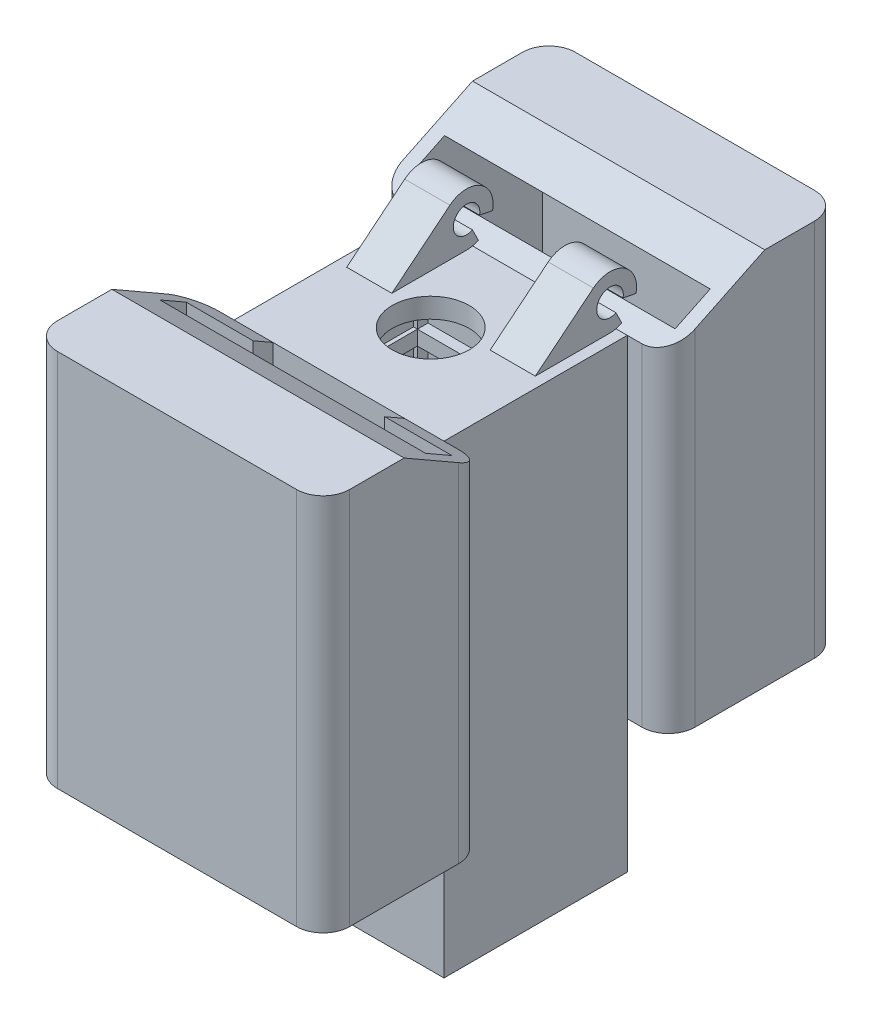
SolidWorks part; units mm, degrees
ref_plane "前视基准面" through (0, 0, 0) normal (0, 0, 1) x (1, 0, 0)
ref_plane "上视基准面" through (0, 0, 0) normal (0, 1, 0) x (1, 0, 0)
ref_plane "右视基准面" through (0, 0, 0) normal (1, 0, 0) x (0, 0, -1)
sketch "草图1" plane through (0, 0, 0) normal (0, 1, 0) x (1, 0, 0)
  line L1 (-4.3182, 2.8513) -> (8.4818, 2.8513)
  line L2 (-4.3182, 2.8513) -> (-4.3182, -7.9487)
  line L3 (-4.3182, -7.9487) -> (8.4818, -7.9487)
  line L4 (8.4818, 2.8513) -> (8.4818, -7.9487)
  dimension "D1" = 12.8
extrude "凸台-拉伸1" add sketch "草图1" along normal blind 1.5
sketch "草图2" plane through (0, 1.5, 0) normal (0, 1, 0) x (1, 0, 0)
  circle A0 centre (2.0818, -2.5487) radius 2.9
extrude "切除-拉伸1" cut sketch "草图2" against normal up to next
sketch "草图3" plane through (0, 1.5, 0) normal (0, 1, 0) x (1, 0, 0)
  line L0 (-4.3182, -2.5487) -> (9.9215, -2.5487) construction
  line L1 (-4.3182, 2.8513) -> (8.4818, 2.8513)
  line L2 (-4.3182, 2.8513) -> (-4.3182, 4.3513)
  line L3 (-4.3182, 4.3513) -> (8.4818, 4.3513)
  line L4 (8.4818, 2.8513) -> (8.4818, 4.3513)
  line L5 (-4.3182, 2.8513) -> (-4.3182, -7.9487) construction
  line L6 (8.4818, -7.9487) -> (8.4818, -9.4487)
  line L7 (-4.3182, -9.4487) -> (8.4818, -9.4487)
  line L8 (-4.3182, -7.9487) -> (-4.3182, -9.4487)
  line L9 (-4.3182, -7.9487) -> (8.4818, -7.9487)
  line L10 (2.0818, 2.8513) -> (2.0818, -17.0231) construction
  line L11 (-4.3182, 4.3513) -> (-5.8182, 4.3513)
  line L12 (-4.3182, 4.3513) -> (-4.3182, -9.4487)
  line L13 (-4.3182, -9.4487) -> (-5.8182, -9.4487)
  line L14 (-5.8182, 4.3513) -> (-5.8182, -9.4487)
  line L15 (8.4818, -9.4487) -> (9.9818, -9.4487)
  line L16 (9.9818, 4.3513) -> (9.9818, -9.4487)
  line L17 (8.4818, 4.3513) -> (8.4818, -9.4487)
  line L18 (8.4818, 4.3513) -> (9.9818, 4.3513)
  line M6 (-4.3182, 2.8513) -> (-4.3182, -7.9487)
  line M7 (-4.3182, -7.9487) -> (8.4818, -7.9487)
  line M8 (8.4818, -7.9487) -> (8.4818, 2.8513)
  line M9 (8.4818, 2.8513) -> (-4.3182, 2.8513)
  dimension "D1" = 1.5
  dimension "D2" = 12.8
  dimension "D3" = 1.5
extrude "凸台-拉伸2" add sketch "草图3" against normal blind 35 contours L11 L14 L13 L8 L2 M6 | L4 L3 L2 M9 | L18 L4 L6 L15 L16 M8 | L8 L7 L6 M7
sketch "草图6" plane through (0, -33.5, 0) normal (0, -1, 0) x (1, 0, 0)
  line L0 (9.9818, -4.3513) -> (-5.8182, -4.3513) construction
  line L1 (-4.3182, -2.8513) -> (8.4818, -2.8513)
  line L2 (-4.3182, -2.8513) -> (-4.3182, -4.3513)
  line L3 (-4.3182, -4.3513) -> (8.4818, -4.3513)
  line L4 (8.4818, -2.8513) -> (8.4818, -4.3513)
extrude "切除-拉伸2" cut sketch "草图6" against normal blind 10
sketch "草图9" plane through (9.9818, 0, 0) normal (1, 0, 0) x (0, 0, -1)
  line L0 (4.3513, 1.5) -> (-9.4487, 1.5) construction
  line L3 (4.3513, -33.5) -> (4.3513, 1.5) construction
  line L5 (4.295, 2.6038) -> (4.7386, 1.7076)
  line L6 (4.8305, 3.2974) -> (5.8108, 3.0999)
  line L10 (-1.7717, 1.5) -> (3.8513, 1.5)
  line L11 (2.5983, 5.0589) -> (-1.7717, 1.5)
  arc A0 (3.8513, 1.5) -> (4.7386, 1.7076) centre (3.8513, 3.5) ccw
  arc A1 (4.8305, 3.2974) -> (4.295, 2.6038) centre (3.8513, 3.5) ccw
  arc A2 (5.8108, 3.0999) -> (2.5983, 5.0589) centre (3.8513, 3.5) ccw
  dimension "D1" = 4
  dimension "D3" = 2
  dimension "D2" = 2
  dimension "D4" = 0.5
extrude "凸台-拉伸4" add sketch "草图9" against normal blind 15.8
sketch "草图10" plane through (0, 0, -4.3513) normal (0, 0, -1) x (-1, 0, 0)
  line L0 (-2.0818, 8.9772) -> (-2.0818, 5.5) construction
  line L1 (-9.9818, 1.5) -> (5.8182, 1.5) construction
  line L2 (1.6182, 1.5) -> (-5.7818, 1.5)
  line L4 (1.6182, 5.5) -> (-5.7818, 5.5)
  line L5 (-5.7818, 1.5) -> (-5.7818, 5.5)
  line L6 (1.6182, 1.5) -> (1.6182, 5.5)
  line L7 (-2.0818, 1.5) -> (-2.0818, -41.1456) construction
  line L8 (5.8182, 1.5) -> (5.0182, 1.5)
  line L9 (-9.9818, 1.5) -> (-9.1818, 1.5)
  line L10 (-9.9818, 1.5) -> (-9.9818, 5.5)
  line L11 (-9.9818, 5.5) -> (-9.1818, 5.5)
  line L12 (-9.1818, 1.5) -> (-9.1818, 5.5)
  line L13 (5.0182, 1.5) -> (5.0182, 5.5)
  line L14 (5.8182, 5.5) -> (5.0182, 5.5)
  line L15 (5.8182, 1.5) -> (5.8182, 5.5)
  dimension "D1" = 3.7
  dimension "D2" = 0.8
  dimension "D3" = 4
  dimension "D4" = 4
extrude "切除-拉伸3" cut sketch "草图10" against normal through all both and the other way through all
sketch "草图12" plane through (0, 0, -4.3513) normal (0, 0, -1) x (-1, 0, 0)
  line L1 (-10.6818, 5.5) -> (6.3182, 5.5)
  line L2 (-10.6818, 5.5) -> (-10.6818, -23.5)
  line L3 (-10.6818, -23.5) -> (6.3182, -23.5)
  line L4 (6.3182, 5.5) -> (6.3182, -23.5)
  line L5 (4.3182, -23.5) -> (-8.4818, -23.5) construction
  line L6 (5.8182, -33.5) -> (5.8182, 1.5) construction
  dimension "D1" = 17
  dimension "D2" = 29
  dimension "D3" = 0
  dimension "D4" = 0.5
sketch "草图16" plane through (0, 0, 0) normal (0, -1, 0) x (1, 0, 0)
  line L1 (-3.9182, 7.5487) -> (8.0818, 7.5487)
  line L2 (-3.9182, 7.5487) -> (-3.9182, -2.4513)
  line L3 (-3.9182, -2.4513) -> (8.0818, -2.4513)
  line L4 (8.0818, 7.5487) -> (8.0818, -2.4513)
  line L5 (-3.9182, 7.5487) -> (8.0818, -2.4513) construction
  line L6 (-3.9182, -2.4513) -> (8.0818, 7.5487) construction
  point P2 (2.0818, 2.5487)
  dimension "D1" = 12
  dimension "D2" = 10
sketch "草图17" plane through (-5.8182, 0, 0) normal (-1, 0, 0) x (0, 0, 1)
  line L0 (-4.3513, -33.5) -> (-4.3513, 1.5) construction
  line L1 (-4.3513, -23.5) -> (-17.3513, -23.5)
  line L2 (-4.3513, -23.5) -> (-4.3513, 1.5)
  line L3 (-11.6013, 5) -> (-17.3513, 5)
  line L4 (-17.3513, -23.5) -> (-17.3513, 5)
  line L5 (-4.3513, -33.5) -> (9.4487, -33.5) construction
  line L6 (-11.6013, 5) -> (-4.3513, 1.5)
  dimension "D1" = 28.5
  dimension "D2" = 13
  dimension "D3" = 10
extrude "凸台-拉伸5" add sketch "草图17" along normal blind 3.1 and the other way blind 18.9
sketch "草图18" plane through (0, -23.5, 0) normal (0, -1, 0) x (1, 0, 0)
  line L8 (-8.9182, -17.3513) -> (-8.9182, -4.3513) construction
  line L9 (-7.9182, -5.8513) -> (12.0818, -5.8513)
  line L10 (-7.9182, -5.8513) -> (-7.9182, -15.8513)
  line L11 (-7.9182, -15.8513) -> (12.0818, -15.8513)
  line L12 (12.0818, -5.8513) -> (12.0818, -15.8513)
  line L13 (13.0818, -17.3513) -> (13.0818, -4.3513) construction
  line L14 (13.0818, -4.3513) -> (9.9818, -4.3513) construction
  line L15 (13.0818, -17.3513) -> (-8.9182, -17.3513) construction
  dimension "D1" = 1
  dimension "D2" = 1
  dimension "D3" = 1.5
  dimension "D4" = 1.5
extrude "切除-拉伸4" cut sketch "草图18" against normal blind 27
sketch "草图20" plane through (0, 0, -2.8513) normal (0, 0, 1) x (1, 0, 0)
  line L0 (8.4818, -23.5) -> (8.4818, 0) construction
  line L1 (8.4818, -11.75) -> (-4.3182, -11.75)
  line L2 (8.4818, -11.75) -> (8.4818, -23.5)
  line L3 (8.4818, -23.5) -> (-4.3182, -23.5)
  line L4 (-4.3182, -11.75) -> (-4.3182, -23.5)
extrude "切除-拉伸5" cut sketch "草图20" against normal up to next
fillet "圆角3" radius 2 4 edges at (13.0818, -11, -4.3513) (13.0818, -9.25, -17.3513) (-8.9182, -9.25, -17.3513) (-8.9182, -11, -4.3513)
sketch "草图21" plane through (0, 0, 7.9487) normal (0, 0, -1) x (-1, 0, 0)
  line L1 (-8.4818, 0) -> (4.3182, 0)
  line L2 (-8.4818, 0) -> (-8.4818, -33.5)
  line L3 (-8.4818, -33.5) -> (4.3182, -33.5)
  line L4 (4.3182, 0) -> (4.3182, -33.5)
extrude "凸台-拉伸6" add sketch "草图21" along normal blind 0.8
sketch "草图22" plane through (0, 0, 7.1487) normal (0, 0, -1) x (-1, 0, 0)
  line L0 (4.3182, -33.5) -> (4.3182, 0) construction
  line L1 (-8.4818, -33.5) -> (4.3182, -33.5)
  line L2 (-8.4818, -33.5) -> (-8.4818, -23.5)
  line L3 (-8.4818, -23.5) -> (4.3182, -23.5)
  line L4 (4.3182, -33.5) -> (4.3182, -23.5)
  dimension "D1" = 10
extrude "切除-拉伸6" cut sketch "草图22" against normal blind 0.8
sketch "草图23" plane through (0, 0, 7.1487) normal (0, 0, -1) x (-1, 0, 0)
  line L0 (-8.4818, 0) -> (-8.4818, -23.5) construction
  line L1 (-8.4818, -2.5) -> (4.3182, -2.5)
  line L2 (-8.4818, -2.5) -> (-8.4818, -4.5)
  line L3 (-8.4818, -4.5) -> (4.3182, -4.5)
  line L4 (4.3182, -2.5) -> (4.3182, -4.5)
  line L5 (4.3182, -23.5) -> (4.3182, 0) construction
  line L6 (4.3182, 0) -> (-8.4818, 0) construction
  dimension "D1" = 2.5
  dimension "D2" = 4.5
extrude "切除-拉伸7" cut sketch "草图23" against normal blind 0.8
sketch "草图25" plane through (0, 0, -2.8513) normal (0, 0, 1) x (1, 0, 0)
  line L0 (-4.3182, -11.75) -> (-4.3182, 0) construction
  line L1 (-4.3182, -2.5) -> (8.4818, -2.5)
  line L2 (-4.3182, -2.5) -> (-4.3182, -4.5)
  line L3 (-4.3182, -4.5) -> (8.4818, -4.5)
  line L4 (8.4818, -2.5) -> (8.4818, -4.5)
  line L5 (8.4818, -11.75) -> (8.4818, 0) construction
  line L6 (8.4818, 0) -> (-4.3182, 0) construction
  dimension "D1" = 2.5
  dimension "D2" = 4.5
extrude "切除-拉伸8" cut sketch "草图25" against normal blind 0.8
sketch "草图26" plane through (0, 0, 7.1487) normal (0, 0, -1) x (-1, 0, 0)
  line L0 (-8.4818, -4.5) -> (-8.4818, -23.5) construction
  line L1 (-8.4818, -5.6) -> (4.3182, -5.6)
  line L2 (-8.4818, -5.6) -> (-8.4818, -7.6)
  line L3 (-8.4818, -7.6) -> (4.3182, -7.6)
  line L4 (4.3182, -5.6) -> (4.3182, -7.6)
  line L5 (4.3182, -23.5) -> (4.3182, -4.5) construction
  line L6 (4.3182, 0) -> (-8.4818, 0) construction
  dimension "D1" = 5.6
  dimension "D2" = 7.6
extrude "切除-拉伸9" cut sketch "草图26" against normal blind 0.8
sketch "草图27" plane through (0, 0, -2.8513) normal (0, 0, 1) x (1, 0, 0)
  line L0 (-4.3182, -11.75) -> (-4.3182, -4.5) construction
  line L1 (-4.3182, -5.6) -> (8.4818, -5.6)
  line L2 (-4.3182, -5.6) -> (-4.3182, -7.6)
  line L3 (-4.3182, -7.6) -> (8.4818, -7.6)
  line L4 (8.4818, -5.6) -> (8.4818, -7.6)
  line L5 (8.4818, -11.75) -> (8.4818, -4.5) construction
  line L6 (8.4818, 0) -> (-4.3182, 0) construction
  dimension "D1" = 5.6
  dimension "D2" = 7.6
extrude "切除-拉伸10" cut sketch "草图27" against normal blind 0.8
sketch "草图28" plane through (-4.3182, 0, 0) normal (1, 0, 0) x (0, 0, -1)
  line L1 (-7.1487, -5.6) -> (2.8513, -5.6)
  line L2 (-7.1487, -5.6) -> (-7.1487, -7.6)
  line L3 (-7.1487, -7.6) -> (2.8513, -7.6)
  line L4 (2.8513, -5.6) -> (2.8513, -7.6)
  line L5 (-7.1487, -2.5) -> (2.8513, -2.5)
  line L6 (-7.1487, -2.5) -> (-7.1487, -4.5)
  line L7 (-7.1487, -4.5) -> (2.8513, -4.5)
  line L8 (2.8513, -2.5) -> (2.8513, -4.5)
extrude "切除-拉伸11" cut sketch "草图28" against normal blind 0.3
sketch "草图29" plane through (8.4818, 0, 0) normal (-1, 0, 0) x (0, 0, 1)
  line L1 (-2.8513, -2.5) -> (7.1487, -2.5)
  line L2 (-2.8513, -2.5) -> (-2.8513, -4.5)
  line L3 (-2.8513, -4.5) -> (7.1487, -4.5)
  line L4 (7.1487, -2.5) -> (7.1487, -4.5)
  line L5 (-2.8513, -5.6) -> (7.1487, -5.6)
  line L6 (-2.8513, -5.6) -> (-2.8513, -7.6)
  line L7 (-2.8513, -7.6) -> (7.1487, -7.6)
  line L8 (7.1487, -5.6) -> (7.1487, -7.6)
extrude "切除-拉伸12" cut sketch "草图29" against normal blind 0.3
sketch "草图30" plane through (0, 0, 9.4487) normal (0, 0, 1) x (1, 0, 0)
  line L1 (-8.9182, -23.5) -> (13.0818, -23.5)
  line L2 (-8.9182, -23.5) -> (-8.9182, 5)
  line L3 (-8.9182, 5) -> (13.0818, 5)
  line L4 (13.0818, -23.5) -> (13.0818, 5)
extrude "凸台-拉伸7" add sketch "草图30" along normal blind 12.2
sketch "草图32" plane through (0, -23.5, 0) normal (0, -1, 0) x (1, 0, 0)
  line L0 (-8.9182, 21.6487) -> (13.0818, 21.6487) construction
  line L1 (-7.9182, 20.1487) -> (12.0818, 20.1487)
  line L2 (-7.9182, 20.1487) -> (-7.9182, 10.9487)
  line L3 (-7.9182, 10.9487) -> (12.0818, 10.9487)
  line L4 (12.0818, 20.1487) -> (12.0818, 10.9487)
  line L5 (13.0818, 21.6487) -> (13.0818, 9.4487) construction
  line L6 (-8.9182, 21.6487) -> (-8.9182, 9.4487) construction
  line L7 (-5.8182, 9.4487) -> (9.9818, 9.4487) construction
  dimension "D1" = 1.5
  dimension "D2" = 1
  dimension "D3" = 1
  dimension "D4" = 1.5
extrude "切除-拉伸13" cut sketch "草图32" against normal blind 27
sketch "草图33" plane through (13.0818, 0, 0) normal (1, 0, 0) x (0, 0, -1)
  line L0 (-15.5487, 5) -> (-9.4487, 1.5)
  line L1 (-21.6487, 5) -> (-9.4487, 5) construction
  line L2 (-9.4487, 1.5) -> (-9.4487, 5)
  line L3 (-9.4487, 5) -> (-15.5487, 5)
extrude "切除-拉伸14" cut sketch "草图33" against normal through all
sketch "草图34" plane through (0, -23.5, 0) normal (0, -1, 0) x (1, 0, 0)
  line L7 (2.0656, 10.9487) -> (2.0656, 13.3835) construction
  line L8 (9.9818, 9.4487) -> (-5.8182, 9.4487) construction
  line L9 (-2.8844, 10.9487) -> (7.0156, 10.9487)
  line L11 (-2.8844, 9.4487) -> (7.0156, 9.4487)
  line L12 (7.0156, 10.9487) -> (7.0156, 9.4487)
  line L13 (-2.8844, 10.9487) -> (-2.8844, 9.4487)
  dimension "D1" = 4.95
extrude "切除-拉伸15" cut sketch "草图34" against normal through all
fillet "圆角4" radius 2 4 edges at (13.0818, -11, 9.4487) (-8.9182, -11, 9.4487) (13.0818, -9.25, 21.6487) (-8.9182, -9.25, 21.6487)
sketch "草图35" plane through (-5.8182, 0, 0) normal (-1, 0, 0) x (0, 0, 1)
  line L0 (-4.3513, -33.5) -> (-4.3513, -23.5) construction
  line L1 (-4.3513, -31.5) -> (7.9487, -31.5)
  line L2 (-4.3513, -31.5) -> (-4.3513, -29.5)
  line L3 (-4.3513, -29.5) -> (7.9487, -29.5)
  line L4 (7.9487, -31.5) -> (7.9487, -29.5)
  line L5 (9.4487, -33.5) -> (9.4487, -23.5) construction
  line L6 (-4.3513, -33.5) -> (9.4487, -33.5) construction
  dimension "D1" = 1.5
  dimension "D2" = 2
  dimension "D3" = 2
sketch "草图36" plane through (-4.3182, 0, 0) normal (1, 0, 0) x (0, 0, -1)
  line L1 (-7.9487, -29.5) -> (4.3513, -29.5)
  line L2 (-7.9487, -29.5) -> (-7.9487, -31.5)
  line L3 (-7.9487, -31.5) -> (4.3513, -31.5)
  line L4 (4.3513, -29.5) -> (4.3513, -31.5)
sketch "草图37" plane through (8.4818, 0, 0) normal (-1, 0, 0) x (0, 0, 1)
  line L1 (-4.3513, -29.5) -> (7.9487, -29.5)
  line L2 (-4.3513, -29.5) -> (-4.3513, -31.5)
  line L3 (-4.3513, -31.5) -> (7.9487, -31.5)
  line L4 (7.9487, -29.5) -> (7.9487, -31.5)
extrude "切除-拉伸18" cut sketch "草图36" against normal blind 1
extrude "切除-拉伸19" cut sketch "草图37" against normal blind 1
